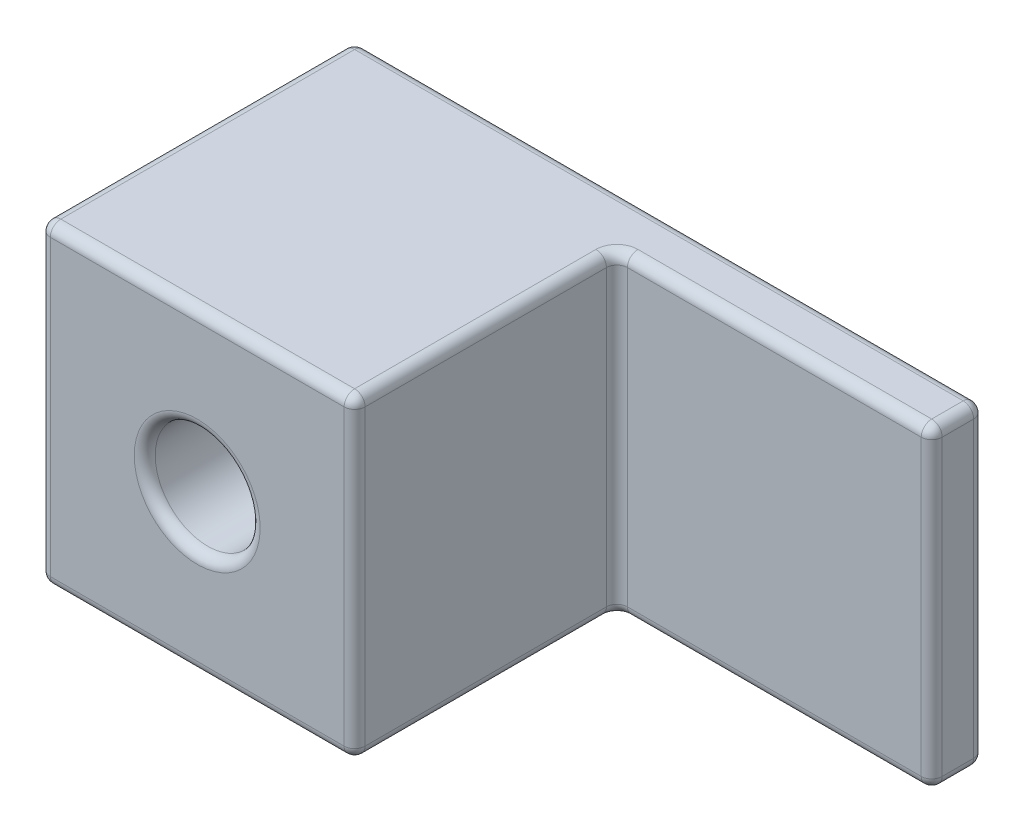
SolidWorks part; units mm, degrees
ref_plane "Front Plane" through (0, 0, 0) normal (0, 0, 1) x (1, 0, 0)
ref_plane "Top Plane" through (0, 0, 0) normal (0, 1, 0) x (1, 0, 0)
ref_plane "Right Plane" through (0, 0, 0) normal (1, 0, 0) x (0, 0, -1)
sketch "Sketch1" plane through (0, 0, 0) normal (0, 0, 1) x (1, 0, 0)
  line L1 (0, 0) -> (60, 0)
  line L2 (0, 0) -> (0, 60)
  line L3 (0, 60) -> (60, 60)
  line L4 (60, 0) -> (60, 60)
  circle A0 centre (30, 30) radius 10
  dimension "D5" = 20
  dimension "D1" = 60
  dimension "D2" = 60
  dimension "D3" = 30
  dimension "D4" = 30
extrude "Boss-Extrude1" add sketch "Sketch1" along normal blind 60
sketch "Sketch2" plane through (60, 0, 0) normal (1, 0, 0) x (0, 0, -1)
  line L0 (-60, 60) -> (0, 60) construction
  line L1 (0, 0) -> (-10, 0)
  line L2 (0, 0) -> (0, 60)
  line L3 (0, 60) -> (-10, 60)
  line L4 (-10, 0) -> (-10, 60)
  dimension "D1" = 10
extrude "Boss-Extrude2" add sketch "Sketch2" along normal blind 60
fillet "Fillet1" radius 2 20 edges at (120, 30, 10) (120, 30, 0) (0, 30, 60) (0, 30, 0) (0, 0, 30) (30, 0, 60) (90, 0, 10) (120, 0, 5) (60, 0, 0) (120, 60, 5) (90, 60, 10) (30, 60, 60) (0, 60, 30) (60, 60, 0) (40, 30, 60) (40, 30, 0) (60, 0, 35) (60, 30, 60) (60, 60, 35) (60, 30, 10)
